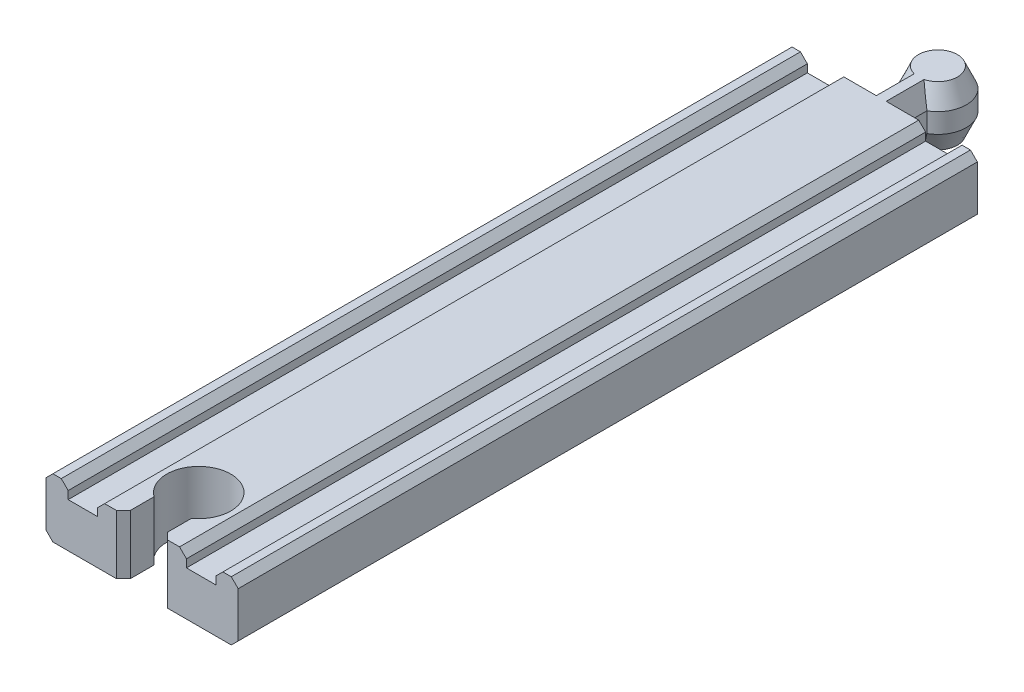
SolidWorks part; units mm, degrees
ref_plane "Front Plane" through (0, 0, 0) normal (0, 0, 1) x (1, 0, 0)
ref_plane "Top Plane" through (0, 0, 0) normal (0, 1, 0) x (1, 0, 0)
ref_plane "Right Plane" through (0, 0, 0) normal (1, 0, 0) x (0, 0, -1)
sketch "Sketch2" plane through (0, 0, 0) normal (0, 0, 1) x (1, 0, 0)
  line L0 (-19.5, 0) -> (19.5, 0)
  line L1 (19.5, 0) -> (19.5, 12)
  line L2 (19.5, 12) -> (15, 12)
  line L3 (15, 12) -> (15, 9)
  line L4 (15, 9) -> (9, 9)
  line L5 (9, 9) -> (9, 12)
  line L6 (9, 12) -> (-9, 12)
  line L7 (-9, 12) -> (-9, 9)
  line L8 (-9, 9) -> (-15, 9)
  line L9 (-15, 9) -> (-15, 12)
  line L10 (-15, 12) -> (-19.5, 12)
  line L11 (-19.5, 12) -> (-19.5, 0)
  point P4 (0, 0)
  point P14 (0, 0)
  dimension "D1" = 39
  dimension "D2" = 12
  dimension "D3" = 3
  dimension "D4" = 4.5
  dimension "D5" = 6
extrude "Boss-Extrude1" add sketch "Sketch2" along normal mid plane 150
sketch "Sketch3" plane through (0, 12, 0) normal (0, 1, 0) x (1, 0, 0)
  line L0 (9, -75) -> (-9, -75) construction
  line L2 (3.8, -75) -> (-3.8, -75)
  line L3 (3.8, -75) -> (3.8, -63.5)
  line L4 (3.8, -63.5) -> (-3.8, -63.5)
  line L5 (-3.8, -75) -> (-3.8, -63.5)
  line L6 (3.8, -75) -> (-3.8, -63.5) construction
  line L7 (3.8, -63.5) -> (-3.8, -75) construction
  circle A0 centre (0, -63.5) radius 6.5
  point P4 (0, -69.25)
  point P5 (0, 0)
  point P11 (0, 0)
  line M1 (-9, -75) -> (9, -75)
  dimension "D1" = 13
  dimension "D2" = 11.5
  dimension "D3" = 7.6
extrude "Cut-Extrude1" cut sketch "Sketch3" against normal through all contours L5 A0 L3 L4 | L3 A0 L5 L4 | A0 L5 L3 M1
chamfer "Chamfer1" distance 1.4 10 edges at (19.5, 0, 0) (19.5, 12, 0) (15, 12, 0) (9, 12, 0) (-9, 12, 0) (-19.5, 0, 0) (-19.5, 12, 0) (-15, 12, 0) (3.8, 6, 75) (-3.8, 6, 75)
sketch "Sketch4" plane through (0, 12, 0) normal (0, 1, 0) x (1, 0, 0)
  line L0 (7.6, 75) -> (-7.6, 75) construction
  line L1 (-2.8, 86.5) -> (2.8, 86.5)
  line L2 (-2.8, 86.5) -> (-2.8, 75)
  line L3 (-2.8, 75) -> (2.8, 75)
  line L4 (2.8, 86.5) -> (2.8, 75)
  line L5 (-2.8, 86.5) -> (2.8, 75) construction
  line L6 (-2.8, 75) -> (2.8, 86.5) construction
  circle A0 centre (0, 86.5) radius 5.75
  point P2 (0, 80.75)
  point P9 (0, 0)
  point P11 (0, 0)
  point P12 (0, 0)
  line M9 (7.6, 75) -> (-7.6, 75)
  dimension "D1" = 11.5
  dimension "D2" = 5.6
  dimension "D3" = 11.5
extrude "Boss-Extrude2" add sketch "Sketch4" against normal up to surface (12 mm away) contours L2 A0 L4 L1 | A0 L2 L4 M9 | L4 A0 L2 L1 up to face at (0, 0, 42.2974)
chamfer "Chamfer2" distance 4 distance2 1.8 6 edges at (0, 0, -92.25) (0, 12, -92.25) (-2.8, 0, -78.2389) (-2.8, 12, -78.2389) (2.8, 0, -78.2389) (2.8, 12, -78.2389)
